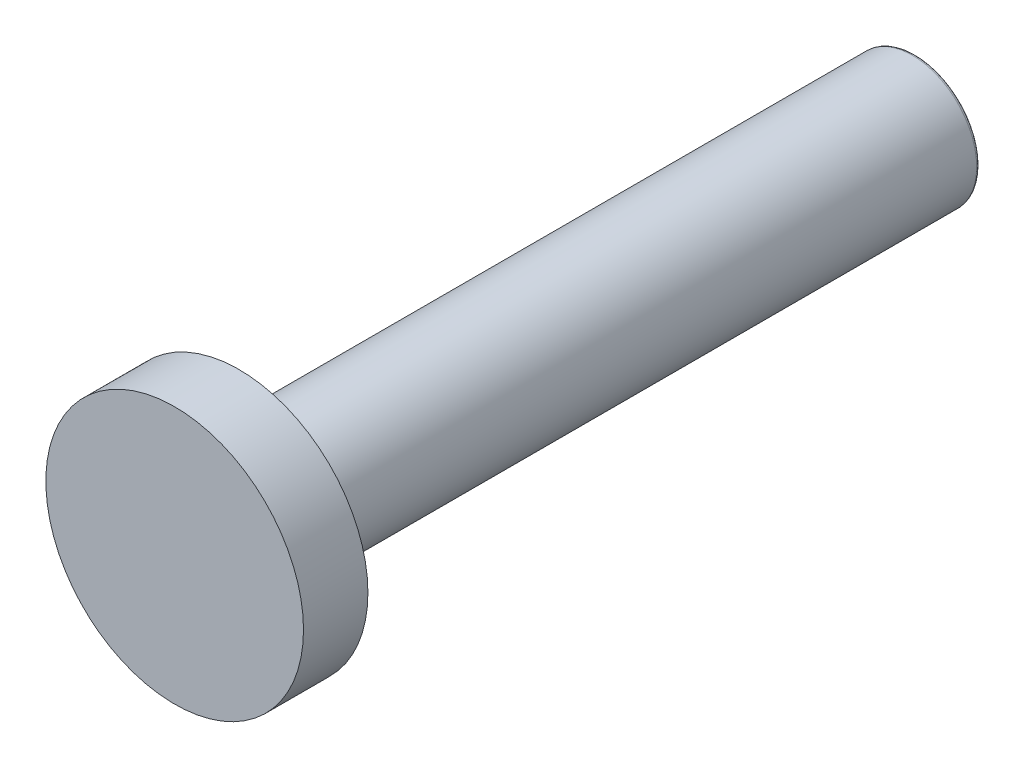
SolidWorks part; units mm, degrees
ref_plane "Front Plane" through (0, 0, 0) normal (0, 0, 1) x (1, 0, 0)
ref_plane "Top Plane" through (0, 0, 0) normal (0, 1, 0) x (1, 0, 0)
ref_plane "Right Plane" through (0, 0, 0) normal (1, 0, 0) x (0, 0, -1)
sketch "Sketch1" plane through (0, 0, 0) normal (0, 1, 0) x (1, 0, 0)
  line L0 (1.8, 0) -> (0, 0)
  line L1 (0, 0) -> (0, -21.7895)
  line L2 (0, -21.7895) -> (3.7895, -21.7895)
  line L3 (3.7895, -21.7895) -> (3.7895, -19.8947)
  line L4 (3.7895, -19.8947) -> (1.8947, -19.8947)
  line L5 (1.8947, -19.8947) -> (1.8947, -0.0947)
  line L6 (0, 0) -> (0, -21.7895) construction
  arc A0 (1.8947, -0.0947) -> (1.8, 0) centre (1.8, -0.0947) ccw
  dimension "D1" = 1.8
revolve "Revolve1" add sketch "Sketch1" angle 360 about L6
